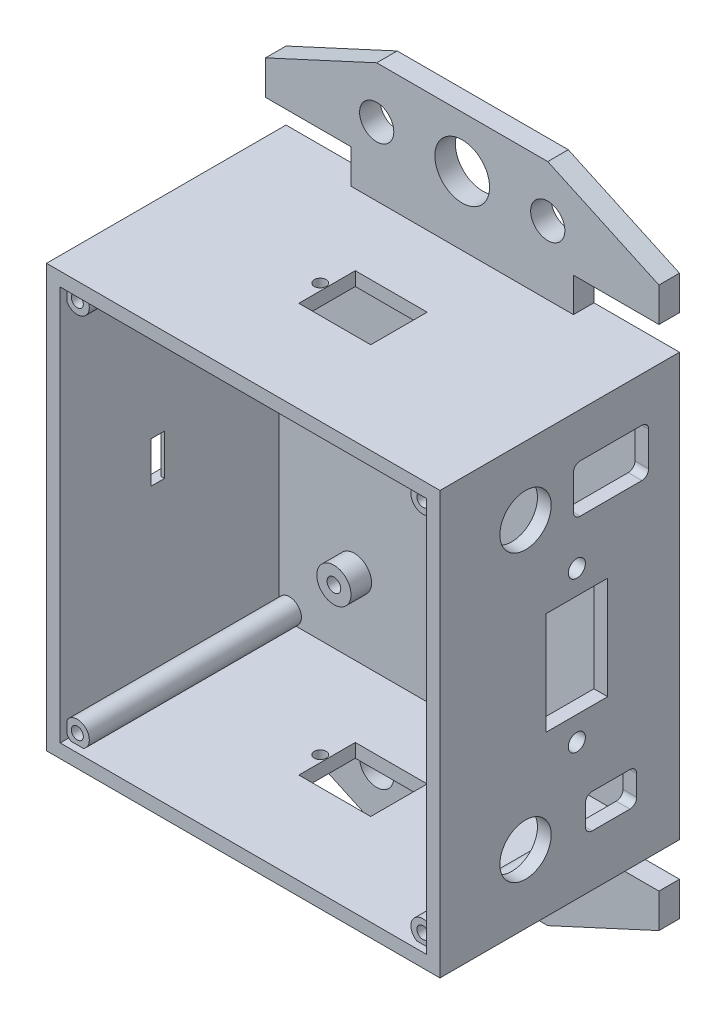
SolidWorks part; units mm, degrees
ref_plane "Alzado" through (0, 0, 0) normal (0, 0, 1) x (1, 0, 0)
ref_plane "Planta" through (0, 0, 0) normal (0, 1, 0) x (1, 0, 0)
ref_plane "Vista lateral" through (0, 0, 0) normal (1, 0, 0) x (0, 0, -1)
sketch "Croquis1" plane through (0, 0, 0) normal (0, 0, 1) x (1, 0, 0)
  line L0 (-7, -7) -> (45, -7) construction
  line L1 (-22, 93.41) -> (85, 93.41)
  line L2 (-7, 78.41) -> (-7, -7) construction
  line L3 (45, -7) -> (45, 78.41) construction
  line L4 (85, 93.41) -> (85, -22)
  line L5 (-22, -22) -> (85, -22)
  line L6 (-22, -22) -> (-22, 93.41)
  line L7 (45, 78.41) -> (-7, 78.41) construction
  circle A0 centre (0, 0) radius 2
  circle A1 centre (38, 0) radius 2
  circle A2 centre (38, 71.41) radius 2
extrude "Saliente-Extruir1" add sketch "Croquis1" along normal blind 6
sketch "Croquis2" plane through (0, 0, 0) normal (0, 0, 1) x (1, 0, 0)
  line L0 (-26, 97.41) -> (89, 97.41)
  line L1 (-22, 93.41) -> (85, 93.41)
  line L2 (89, 97.41) -> (89, -26)
  line L3 (85, 93.41) -> (85, -22)
  line L4 (-26, 97.41) -> (-26, -26)
  line L5 (-26, -26) -> (89, -26)
  line L6 (85, -22) -> (-22, -22)
  line L7 (-22, -22) -> (-22, 93.41)
extrude "Saliente-Extruir2" add sketch "Croquis2" along normal blind 70
ref_plane "Plano1" through (90, 0, 0) normal (1, 0, 0) x (0, 0, -1)
sketch "Croquis3" plane through (90, 0, 0) normal (1, 0, 0) x (0, 0, -1)
  line L2 (-14.5, -1) -> (-25.5, -1)
  line L3 (-12.5, -3) -> (-12.5, -9)
  line L4 (-29, 84.41) -> (-11, 84.41)
  line L5 (-31, 82.41) -> (-31, 72.41)
  line L6 (-29, 70.41) -> (-11, 70.41)
  line L7 (-9, 82.41) -> (-9, 72.41)
  line L8 (-14.5, -11) -> (-25.5, -11)
  line L9 (-27.5, -3) -> (-27.5, -9)
  circle A0 centre (-45, 77.41) radius 7.5
  arc A1 (-11, 84.41) -> (-9, 82.41) centre (-11, 82.41) cw
  arc A2 (-9, 72.41) -> (-11, 70.41) centre (-11, 72.41) cw
  arc A3 (-31, 72.41) -> (-29, 70.41) centre (-29, 72.41) ccw
  arc A4 (-29, 84.41) -> (-31, 82.41) centre (-29, 82.41) ccw
  circle A5 centre (-45, -6) radius 7.5
  arc A6 (-14.5, -11) -> (-12.5, -9) centre (-14.5, -9) ccw
  arc A7 (-12.5, -3) -> (-14.5, -1) centre (-14.5, -3) ccw
  arc A8 (-27.5, -3) -> (-25.5, -1) centre (-25.5, -3) cw
  arc A9 (-27.5, -9) -> (-25.5, -11) centre (-25.5, -9) ccw
extrude "Cortar-Extruir1" cut sketch "Croquis3" against normal blind 51
ref_plane "Plano2" through (0, -30, 0) normal (0, 1, 0) x (1, 0, 0)
sketch "Croquis4" plane through (0, -30, 0) normal (0, 1, 0) x (1, 0, 0)
  line L0 (89, 0) -> (-26, 0) construction
  line L1 (-26, 0) -> (-26, -70) construction
  line L2 (-26, -70) -> (-26, 0) construction
  line L4 (21, -26.75) -> (42, -26.75)
  line L5 (21, -26.75) -> (21, -43.25)
  line L6 (21, -43.25) -> (42, -43.25)
  line L7 (42, -26.75) -> (42, -43.25)
  circle A0 centre (19, -35) radius 1.75
  point P4 (31.5, -35)
extrude "Cortar-Extruir2" cut sketch "Croquis4" along normal blind 166 and the other way blind 31
ref_plane "Plano4" through (-26, 0, 0) normal (1, 0, 0) x (0, 0, -1)
sketch "Croquis6" plane through (-26, 0, 0) normal (1, 0, 0) x (0, 0, -1)
  line L0 (0, -26) -> (0, 97.41) construction
  line L1 (0, 97.41) -> (-70, 97.41) construction
  line L3 (-43.5, 41.705) -> (-26.5, 41.705)
  line L4 (-43.5, 41.705) -> (-43.5, 29.705)
  line L5 (-43.5, 29.705) -> (-26.5, 29.705)
  line L6 (-26.5, 41.705) -> (-26.5, 29.705)
  point P4 (-35, 35.705)
extrude "Cortar-Extruir3" cut sketch "Croquis6" along normal blind 3
sketch "Croquis7" plane through (-26, 0, 0) normal (1, 0, 0) x (0, 0, -1)
  line L0 (-43.5, 29.705) -> (-26.5, 29.705) construction
  line L1 (-43.5, 41.705) -> (-40.5, 41.705)
  line L2 (-43.5, 41.705) -> (-43.5, 29.705)
  line L3 (-43.5, 29.705) -> (-40.5, 29.705)
  line L5 (-43.5, 29.705) -> (-26.5, 29.705) construction
  line L6 (-40.5, 41.705) -> (-39.5, 41.705)
  line L8 (-40.5, 29.705) -> (-39.5, 29.705)
  line L9 (-39.5, 41.705) -> (-39.5, 29.705)
extrude "Cortar-Extruir4" cut sketch "Croquis7" along normal blind 18 and the other way blind 21
sketch "Croquis8" plane through (-26, 0, 0) normal (1, 0, 0) x (0, 0, -1)
  line L0 (0, 97.41) -> (0, -26) construction
  line L1 (0, -26) -> (-70, -26) construction
  line L3 (-50, 55.705) -> (-20, 55.705)
  line L4 (-50, 55.705) -> (-50, 15.705)
  line L5 (-50, 15.705) -> (-20, 15.705)
  line L6 (-20, 55.705) -> (-20, 15.705)
  point P4 (-35, 35.705)
extrude "Cortar-Extruir5" cut sketch "Croquis8" along normal blind 1
sketch "Croquis9" plane through (0, 0, 0) normal (0, 0, 1) x (1, 0, 0)
  circle A0 centre (38, 0) radius 1.9993
  circle A1 centre (38, 0) radius 5
  circle A2 centre (0, 0) radius 2
  circle A3 centre (0, 0) radius 5
  circle A4 centre (38, 71.41) radius 2
  circle A5 centre (38, 71.41) radius 5
extrude "Saliente-Extruir3" add sketch "Croquis9" along normal blind 12
sketch "Croquis10" plane through (0, 0, 0) normal (0, 0, 1) x (1, 0, 0)
  circle A0 centre (38, 71.41) radius 3.5
  circle A1 centre (0, 0) radius 3.5
  circle A2 centre (38, 0) radius 3.5
extrude "Cortar-Extruir6" cut sketch "Croquis10" along normal blind 3
sketch "Croquis11" plane through (0, 0, 0) normal (0, 0, 1) x (1, 0, 0)
  line L0 (-22, 93.41) -> (-19, 93.41) construction
  line L2 (85, 93.41) -> (82, 93.41) construction
  line L3 (85, 93.41) -> (-22, 93.41) construction
  line L5 (85, -22) -> (82, -22) construction
  line L7 (-22, -22) -> (-19, -22) construction
  line L8 (-22, -22) -> (85, -22) construction
  circle A0 centre (-19, -19) radius 3.5
  circle A1 centre (-19, 90.41) radius 3.5
  circle A2 centre (82, 90.41) radius 3.5
  circle A3 centre (82, -19) radius 3.5
  circle A4 centre (-19, 90.41) radius 1.75
  circle A5 centre (-19, -19) radius 1.75
  circle A6 centre (82, -19) radius 1.75
  circle A7 centre (82, 90.41) radius 1.75
extrude "Saliente-Extruir4" add sketch "Croquis11" along normal blind 68
sketch "Croquis12" plane through (0, 0, 0) normal (0, 0, 1) x (1, 0, 0)
  line L0 (64, 97.41) -> (-1, 97.41)
  line L1 (-1, -36) -> (-26, -36)
  line L2 (56.5, 132.41) -> (6.5, 132.41)
  line L3 (64, 97.41) -> (64, 107.41)
  line L4 (64, 107.41) -> (89, 107.41)
  line L5 (-26, -26) -> (89, -26) construction
  line L6 (-1, 97.41) -> (-1, 107.41)
  line L7 (-1, 107.41) -> (-26, 107.41)
  line L8 (89, 107.41) -> (89, 117.41)
  line L9 (64, -26) -> (64, -36)
  line L10 (56.5, -61) -> (6.5, -61)
  line L11 (-1, -36) -> (-1, -26)
  line L12 (-1, -26) -> (64, -26)
  line L13 (-26, -36) -> (-26, -46)
  line L16 (-26, 117.41) -> (-26, 107.41)
  line L17 (6.5, -61) -> (-26, -46)
  line L19 (56.5, -61) -> (89, -46)
  line L20 (89, -46) -> (89, -36)
  line L21 (56.5, 132.41) -> (89, 117.41)
  line L22 (89, -36) -> (64, -36)
  line L23 (6.5, 132.41) -> (-26, 117.41)
  circle A0 centre (56.5, -46) radius 5
  circle A1 centre (31.5, -46) radius 8
  circle A2 centre (6.5, -46) radius 5
  circle A3 centre (56.5, 117.41) radius 5
  circle A4 centre (6.5, 117.41) radius 5
  circle A5 centre (31.5, 117.41) radius 8
  dimension "D1" = 163.41
  dimension "D2" = 115
  dimension "D3" = 193.41
  dimension "D4" = 123.41
  dimension "D5" = 57.5
  dimension "D6" = 82.5
  dimension "D7" = 32.5
extrude "Saliente-Extruir5" add sketch "Croquis12" along normal blind 6
ref_plane "Plano5" through (90, 0, 0) normal (1, 0, 0) x (0, 0, -1)
sketch "Croquis13" plane through (90, 0, 0) normal (1, 0, 0) x (0, 0, -1)
  line L0 (0, 97.41) -> (0, -26) construction
  line L4 (-39, 50.705) -> (-21, 50.705)
  line L5 (-39, 50.705) -> (-39, 20.705)
  line L6 (-39, 20.705) -> (-21, 20.705)
  line L7 (-21, 50.705) -> (-21, 20.705)
  circle A0 centre (-30, 13.705) radius 2.5
  circle A1 centre (-30, 57.705) radius 2.5
extrude "Cortar-Extruir7" cut sketch "Croquis13" against normal blind 10
